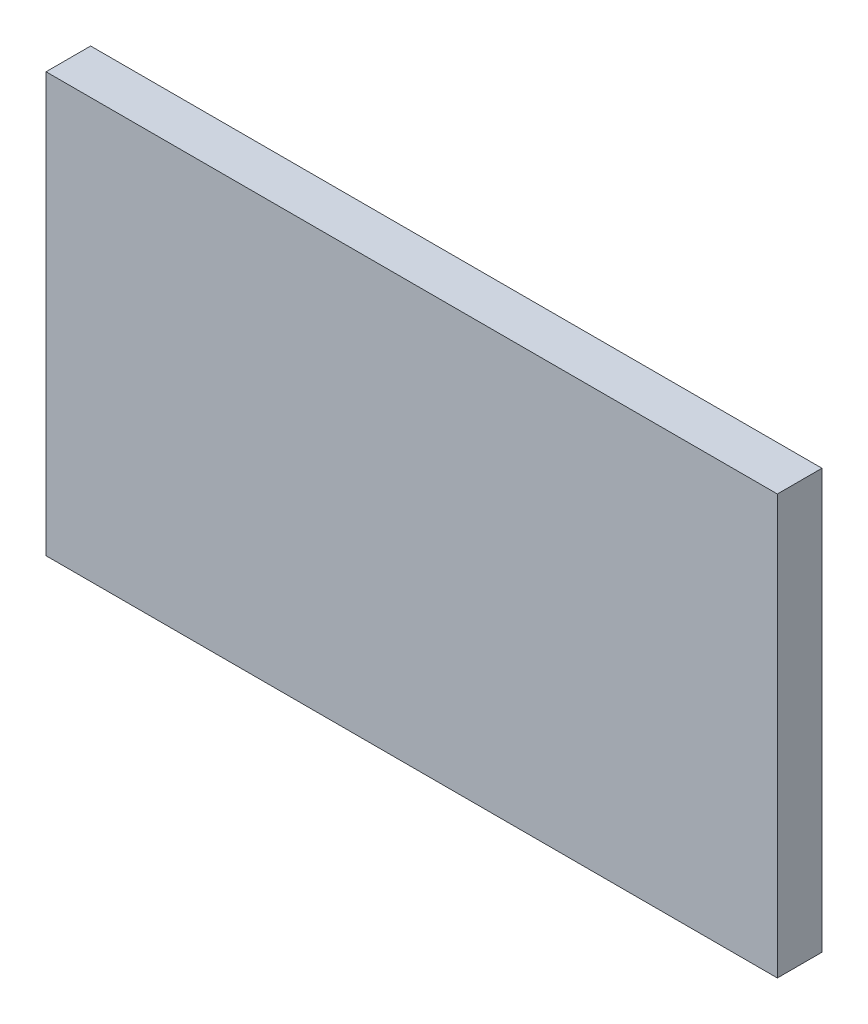
SolidWorks part; units mm, degrees
material "Cuivre"
ref_plane "Plan de face" through (0, 0, 0) normal (0, 0, 1) x (1, 0, 0)
ref_plane "Plan de dessus" through (0, 0, 0) normal (0, 1, 0) x (1, 0, 0)
ref_plane "Plan de droite" through (0, 0, 0) normal (1, 0, 0) x (0, 0, -1)
sketch "Esquisse1" plane through (0, 0, 0) normal (0, 0, 1) x (1, 0, 0)
  line L1 (0, 0) -> (16.4, 0)
  line L2 (0, 0) -> (0, 9.4)
  line L3 (0, 9.4) -> (16.4, 9.4)
  line L4 (16.4, 0) -> (16.4, 9.4)
  dimension "D1" = 9.4
  dimension "D2" = 16.4
extrude "Boss.-Extru.1" add sketch "Esquisse1" along normal blind 1
